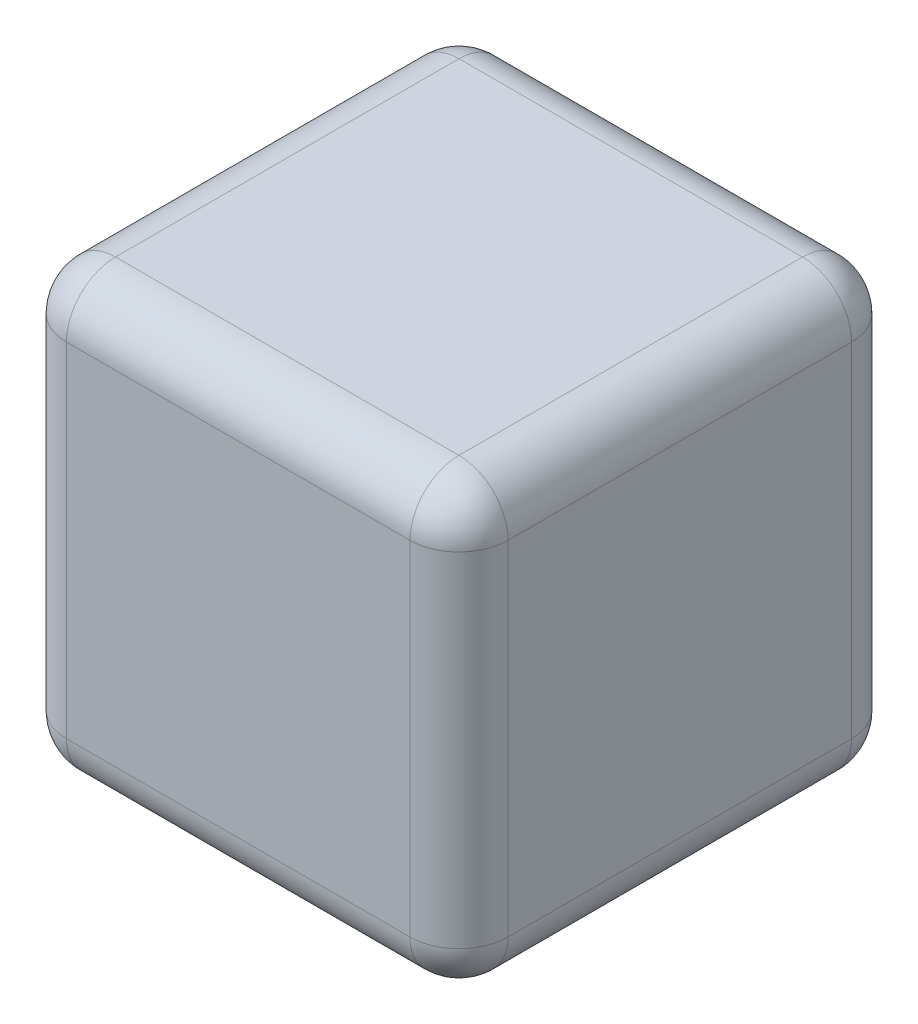
SolidWorks part; units mm, degrees
ref_plane "Front Plane" through (0, 0, 0) normal (0, 0, 1) x (1, 0, 0)
ref_plane "Top Plane" through (0, 0, 0) normal (0, 1, 0) x (1, 0, 0)
ref_plane "Right Plane" through (0, 0, 0) normal (1, 0, 0) x (0, 0, -1)
sketch "Sketch1" plane through (0, 0, 0) normal (1, 0, 0) x (0, 0, -1)
  line L1 (-4.5, 4.5) -> (4.5, 4.5)
  line L2 (-4.5, 4.5) -> (-4.5, -4.5)
  line L3 (-4.5, -4.5) -> (4.5, -4.5)
  line L4 (4.5, 4.5) -> (4.5, -4.5)
  line L5 (-4.5, 4.5) -> (4.5, -4.5) construction
  line L6 (-4.5, -4.5) -> (4.5, 4.5) construction
  point P0 (0, 0)
  dimension "D1" = 9
  dimension "D2" = 9
extrude "Boss-Extrude1" add sketch "Sketch1" along normal mid plane 9
fillet "Fillet1" radius 1 12 edges at (-4.5, 0, 4.5) (-4.5, 0, -4.5) (4.5, 0, 4.5) (4.5, 0, -4.5) (0, -4.5, 4.5) (-4.5, -4.5, 0) (0, -4.5, -4.5) (4.5, -4.5, 0) (-4.5, 4.5, 0) (0, 4.5, -4.5) (4.5, 4.5, 0) (0, 4.5, 4.5)
